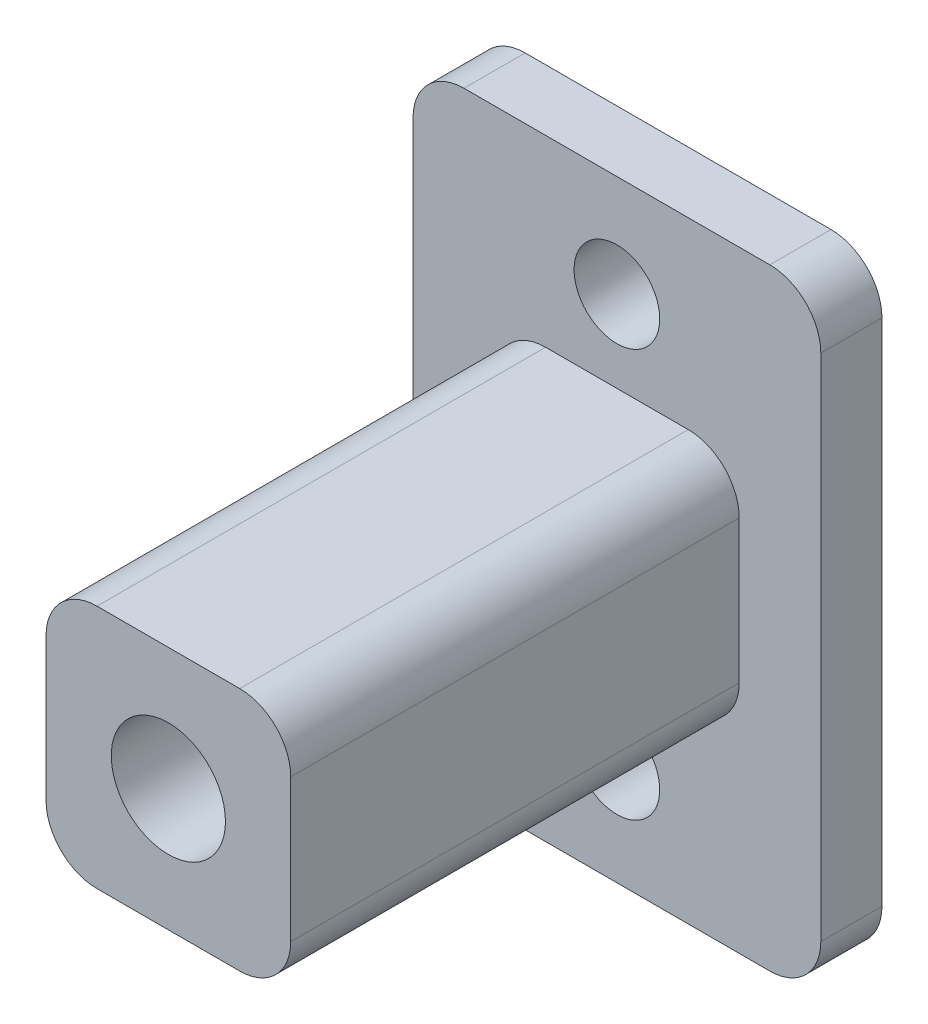
SolidWorks part; units mm, degrees
ref_plane "Plan de face" through (0, 0, 0) normal (0, 0, 1) x (1, 0, 0)
ref_plane "Plan de dessus" through (0, 0, 0) normal (0, 1, 0) x (1, 0, 0)
ref_plane "Plan de droite" through (0, 0, 0) normal (1, 0, 0) x (0, 0, -1)
sketch "Esquisse1" plane through (0, 0, 0) normal (0, 0, 1) x (1, 0, 0)
  line L0 (-10, 0) -> (10, 0) construction
  line L1 (10, -15) -> (-10, -15)
  line L2 (10, -15) -> (10, 15)
  line L3 (10, 15) -> (-10, 15)
  line L4 (-10, -15) -> (-10, 15)
  line L5 (10, -15) -> (-10, 15) construction
  line L6 (10, 15) -> (-10, -15) construction
  line L7 (0, 15) -> (0, -15) construction
  circle A0 centre (0, 10) radius 2.1
  circle A1 centre (0, -10) radius 2.1
  point P0 (0, 0)
  dimension "D3" = 4.2
  dimension "D1" = 20
  dimension "D2" = 30
  dimension "D4" = 5
extrude "Boss.-Extru.1" add sketch "Esquisse1" along normal blind 3
sketch "Esquisse2" plane through (0, 0, 3) normal (0, 0, 1) x (1, 0, 0)
  line L1 (6, -6) -> (-6, -6)
  line L2 (6, -6) -> (6, 6)
  line L3 (6, 6) -> (-6, 6)
  line L4 (-10, 15) -> (-10, -15)
  line L5 (-10, -15) -> (10, -15)
  line L6 (10, -15) -> (10, 15)
  line L7 (10, 15) -> (-10, 15)
  line L8 (-10, 15) -> (-10, -15)
  line L9 (-10, -15) -> (10, -15)
  line L10 (10, -15) -> (10, 15)
  line L11 (10, 15) -> (-10, 15)
  line L12 (-6, -6) -> (-6, 6)
  line L13 (6, -6) -> (-6, 6) construction
  line L14 (6, 6) -> (-6, -6) construction
  point P2 (0, 0)
  point P9 (-6.8367, 6)
  line M8 (-10, 15) -> (-10, -15)
  line M10 (10, -15) -> (10, 15)
  dimension "D2" = 12
  dimension "D1" = 0
extrude "Boss.-Extru.2" add sketch "Esquisse2" along normal blind 22 contours L3 L1 M10 M8
sketch "Esquisse3" plane through (0, 0, 25) normal (0, 0, 1) x (1, 0, 0)
  line L0 (0, 6) -> (0, -6) construction
  line L1 (-6, 0) -> (6, 0) construction
  line L4 (-6, 6) -> (-6, -6)
  line L5 (-6, -6) -> (6, -6)
  line L6 (6, -6) -> (6, 6)
  line L7 (6, 6) -> (-6, 6)
  line L8 (-6, 6) -> (-6, -6)
  line L9 (-6, -6) -> (6, -6)
  line L10 (6, -6) -> (6, 6)
  line L11 (6, 6) -> (-6, 6)
  circle A0 centre (0, 0) radius 2.8
  dimension "D2" = 5.6
  dimension "D1" = 0
extrude "Enlèv. mat.-Extru.1" cut sketch "Esquisse3" against normal blind 9.1 flip side to cut
fillet "Congé1" radius 2.5 8 edges at (10, -15, 1.5) (6, 6, 14) (10, 15, 1.5) (6, -6, 14) (-10, -15, 1.5) (-6, -6, 14) (-6, 6, 14) (-10, 15, 1.5)
